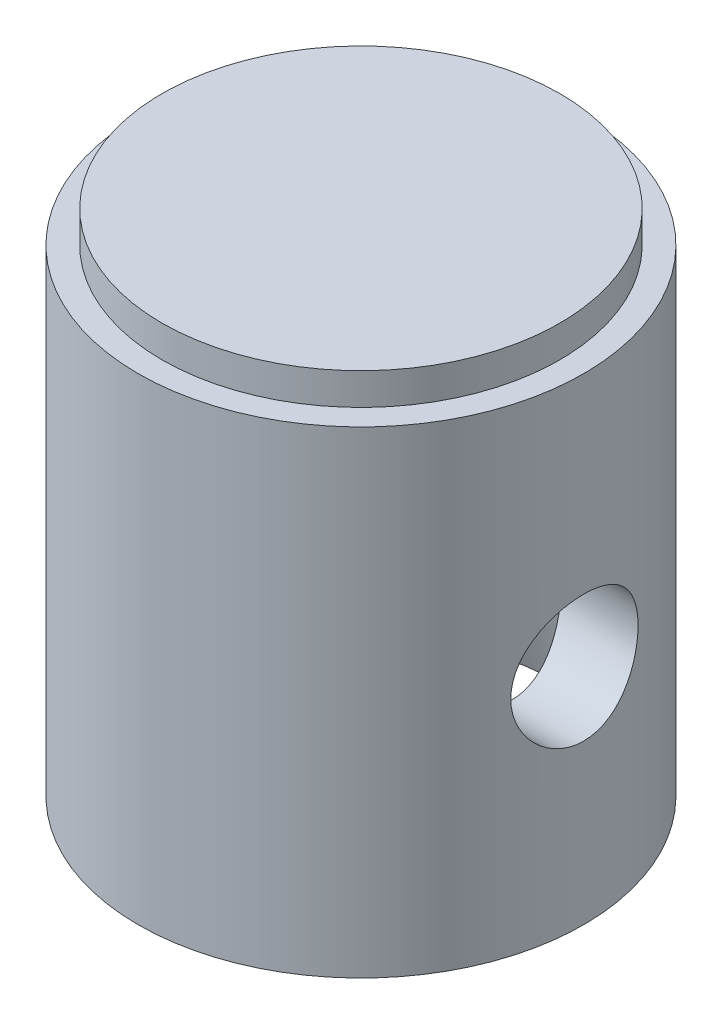
SolidWorks part; units mm, degrees
ref_plane "Front Plane" through (0, 0, 0) normal (0, 0, 1) x (1, 0, 0)
ref_plane "Top Plane" through (0, 0, 0) normal (0, 1, 0) x (1, 0, 0)
ref_plane "Right Plane" through (0, 0, 0) normal (1, 0, 0) x (0, 0, -1)
sketch "Sketch1" plane through (0, 0, 0) normal (0, 0, 1) x (1, 0, 0)
  line L0 (0, 8.1089) -> (0, -8.2822) construction
  line L1 (0, 9.5558) -> (0, 7.4098)
  line L2 (0, 7.4098) -> (4.75, 4.5558)
  line L3 (4.75, 4.5558) -> (4.75, -2.4604)
  line L4 (4.75, -2.4604) -> (6.2, -6.4442)
  line L5 (6.2, -6.4442) -> (7, -6.4442)
  line L6 (7, -6.4442) -> (7, 8.5558)
  line L7 (7, 8.5558) -> (6.25, 8.5558)
  line L8 (6.25, 8.5558) -> (6.25, 9.5558)
  line L9 (6.25, 9.5558) -> (0, 9.5558)
  dimension "D1" = 7
  dimension "D2" = 6.25
  dimension "D3" = 1
  dimension "D4" = 11
  dimension "D5" = 4.75
  dimension "D6" = 59
  dimension "D7" = 6.2
  dimension "D8" = 160
  dimension "D9" = 16
revolve "Revolve1" add sketch "Sketch1" angle 360 about L0
sketch "Sketch2" plane through (0, 0, 0) normal (1, 0, 0) x (0, 0, -1)
  line L0 (-7, -6.4442) -> (7, -6.4442) construction
  circle A0 centre (0, 0.5558) radius 2
  dimension "D1" = 4
  dimension "D2" = 7
extrude "Cut-Extrude1" cut sketch "Sketch2" against normal through all both and the other way through all
